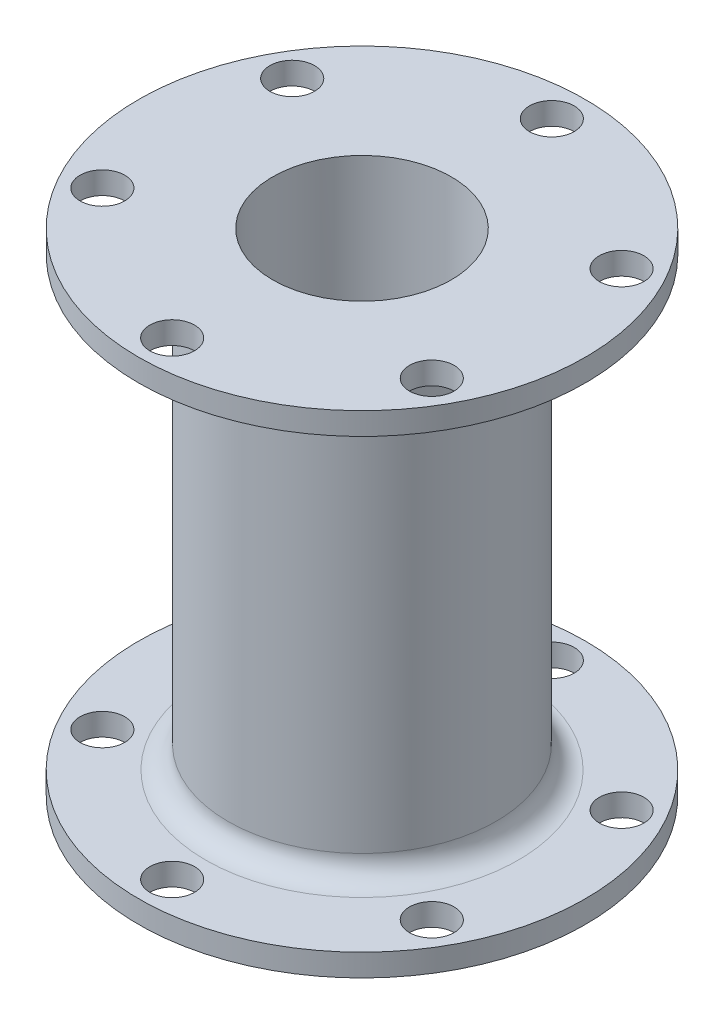
SolidWorks part; units mm, degrees
ref_plane "Front Plane" through (0, 0, 0) normal (0, 0, 1) x (1, 0, 0)
ref_plane "Top Plane" through (0, 0, 0) normal (0, 1, 0) x (1, 0, 0)
ref_plane "Right Plane" through (0, 0, 0) normal (1, 0, 0) x (0, 0, -1)
sketch "Sketch1" plane through (0, 0, 0) normal (0, 1, 0) x (1, 0, 0)
  circle A0 centre (0, 0) radius 127
extrude "Boss-Extrude1" add sketch "Sketch1" along normal blind 12.7
sketch "Sketch2" plane through (0, 12.7, 0) normal (0, 1, 0) x (1, 0, 0)
  circle A0 centre (0, 107.95) radius 12.7
  circle A1 centre (0, -107.95) radius 12.7
  circle A2 centre (93.6625, 53.975) radius 12.7
  circle A3 centre (-93.6625, 53.975) radius 12.7
  circle A4 centre (-93.6625, -53.975) radius 12.7
  circle A5 centre (93.6625, -53.975) radius 12.7
  dimension "D1" = 107.95
  dimension "D2" = 107.95
  dimension "D3" = 93.6625
  dimension "D4" = 93.6625
  dimension "D5" = 53.975
  dimension "D6" = 53.975
  dimension "D7" = 53.975
  dimension "D8" = 53.975
  dimension "D9" = 93.6625
  dimension "D10" = 93.6625
extrude "Cut-Extrude1" cut sketch "Sketch2" against normal blind 12.7
sketch "Sketch3" plane through (0, 0, 0) normal (0, -1, 0) x (1, 0, 0)
  circle A0 centre (0, 0) radius 76.2
extrude "Boss-Extrude2" add sketch "Sketch3" along normal blind 254
sketch "Sketch4" plane through (0, -254, 0) normal (0, -1, 0) x (1, 0, 0)
  circle A0 centre (0, 0) radius 127
extrude "Boss-Extrude3" add sketch "Sketch4" along normal blind 12.7
sketch "Sketch5" plane through (0, -266.7, 0) normal (0, -1, 0) x (1, 0, 0)
  circle A0 centre (0, 107.95) radius 12.7
  circle A1 centre (0, -107.95) radius 12.7
  circle A2 centre (-93.6625, 53.975) radius 12.7
  circle A3 centre (-93.6625, -53.975) radius 12.7
  circle A4 centre (93.6625, 53.975) radius 12.7
  circle A5 centre (93.6625, -53.975) radius 12.7
  point P15 (0, 0)
  dimension "D1" = 107.95
  dimension "D9" = 93.6625
  dimension "D2" = 107.95
  dimension "D3" = 93.6625
  dimension "D4" = 53.975
  dimension "D5" = 53.975
  dimension "D6" = 53.975
  dimension "D7" = 53.975
  dimension "D8" = 93.6625
  dimension "D10" = 93.6625
extrude "Cut-Extrude2" cut sketch "Sketch5" against normal blind 12.7
fillet "Fillet1" radius 12.7 2 edges at (0, -254, -76.2) (0, 0, 76.2)
sketch "Sketch6" plane through (0, 12.7, 0) normal (0, 1, 0) x (1, 0, 0)
  circle A0 centre (0, 0) radius 50.8
extrude "Cut-Extrude3" cut sketch "Sketch6" against normal blind 1397
